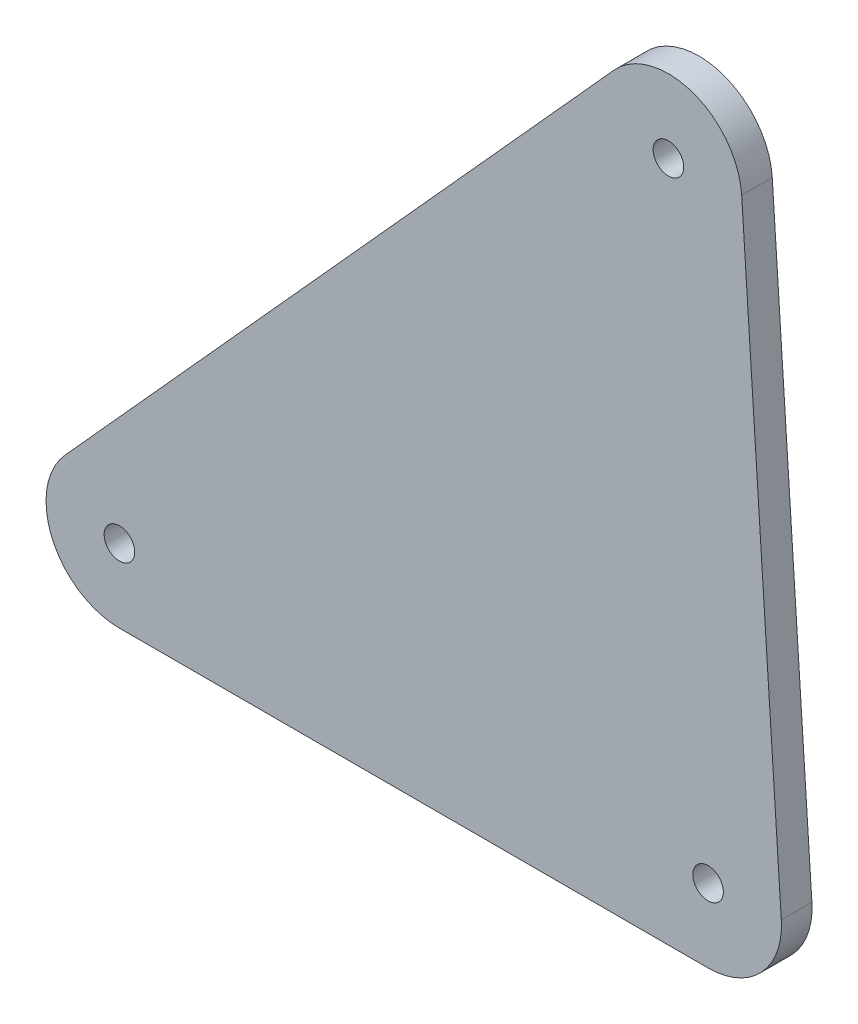
SolidWorks part; units mm, degrees
ref_plane "前视基准面" through (0, 0, 0) normal (0, 0, 1) x (1, 0, 0)
ref_plane "上视基准面" through (0, 0, 0) normal (0, 1, 0) x (1, 0, 0)
ref_plane "右视基准面" through (0, 0, 0) normal (1, 0, 0) x (0, 0, -1)
ref_plane "基准面4" through (0, 0, -18.206) normal (0, 0, 1) x (1, 0, 0)
sketch "草图1" plane through (0, 0, -18.206) normal (0, 0, 1) x (1, 0, 0)
  line L0 (108.2146, -42.9134) -> (101.7322, 56.4754)
  line L1 (80.8518, 63.7372) -> (-8.9058, -35.6516)
  line L2 (0, -55.6944) -> (96.24, -55.6944)
  circle A0 centre (89.7576, 55.6944) radius 2.5
  circle A1 centre (96.24, -43.6944) radius 2.5
  circle A2 centre (0, -43.6944) radius 2.5
  arc A3 (101.7322, 56.4754) -> (80.8518, 63.7372) centre (89.7576, 55.6944) ccw
  arc A4 (-8.9058, -35.6516) -> (0, -55.6944) centre (0, -43.6944) ccw
  arc A5 (96.24, -55.6944) -> (108.2146, -42.9134) centre (96.24, -43.6944) ccw
  dimension "D1" = 5
  dimension "D2" = 5
  dimension "D3" = 5
extrude "凸台-拉伸1" add sketch "草图1" against normal blind 5
